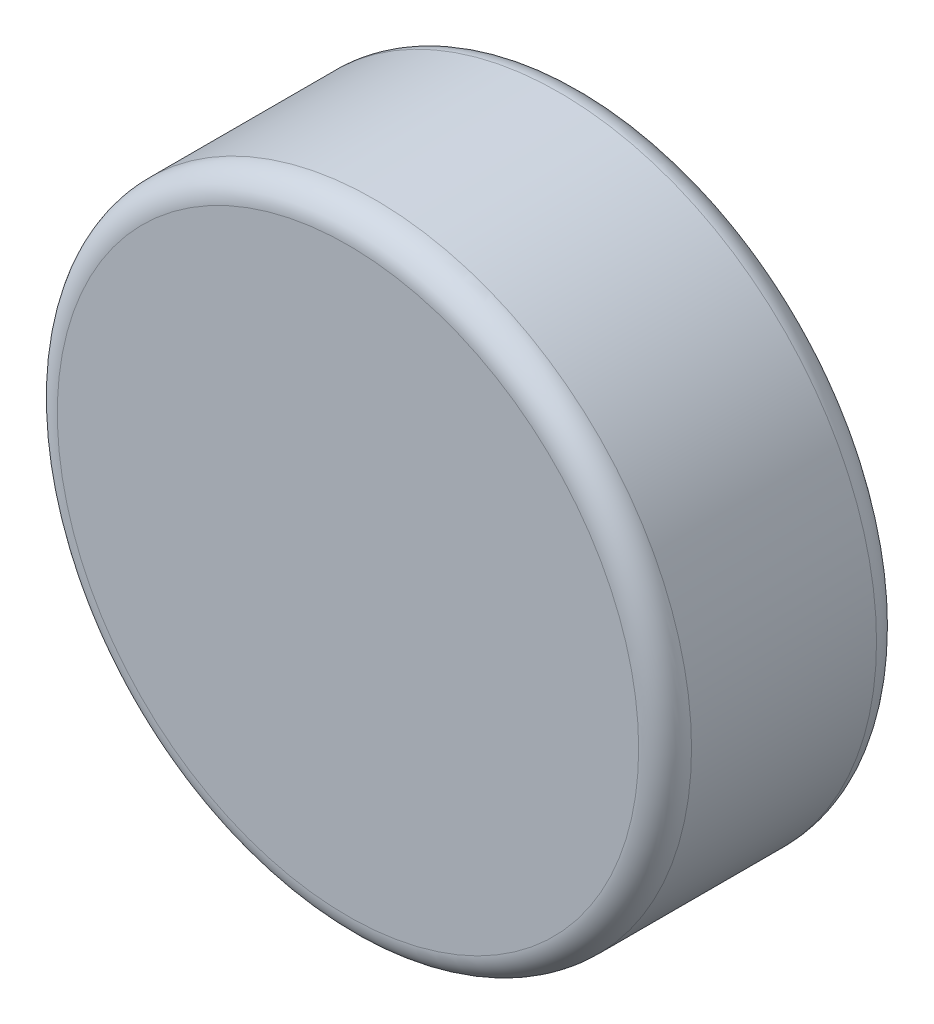
SolidWorks part; units mm, degrees
ref_plane "Front Plane" through (0, 0, 0) normal (0, 0, 1) x (1, 0, 0)
ref_plane "Top Plane" through (0, 0, 0) normal (0, 1, 0) x (1, 0, 0)
ref_plane "Right Plane" through (0, 0, 0) normal (1, 0, 0) x (0, 0, -1)
sketch "Sketch1" plane through (0, 0, 0) normal (0, 0, 1) x (1, 0, 0)
  circle A0 centre (0, 0) radius 30.48
  dimension "D1" = 60.96
extrude "Boss-Extrude2" add sketch "Sketch1" along normal blind 22.86 contours A0
fillet "Fillet1" radius 2.54 1 edges at (30.48, 0, 22.86)
fillet "Fillet2" radius 2.54 1 edges at (30.48, 0, 0)
